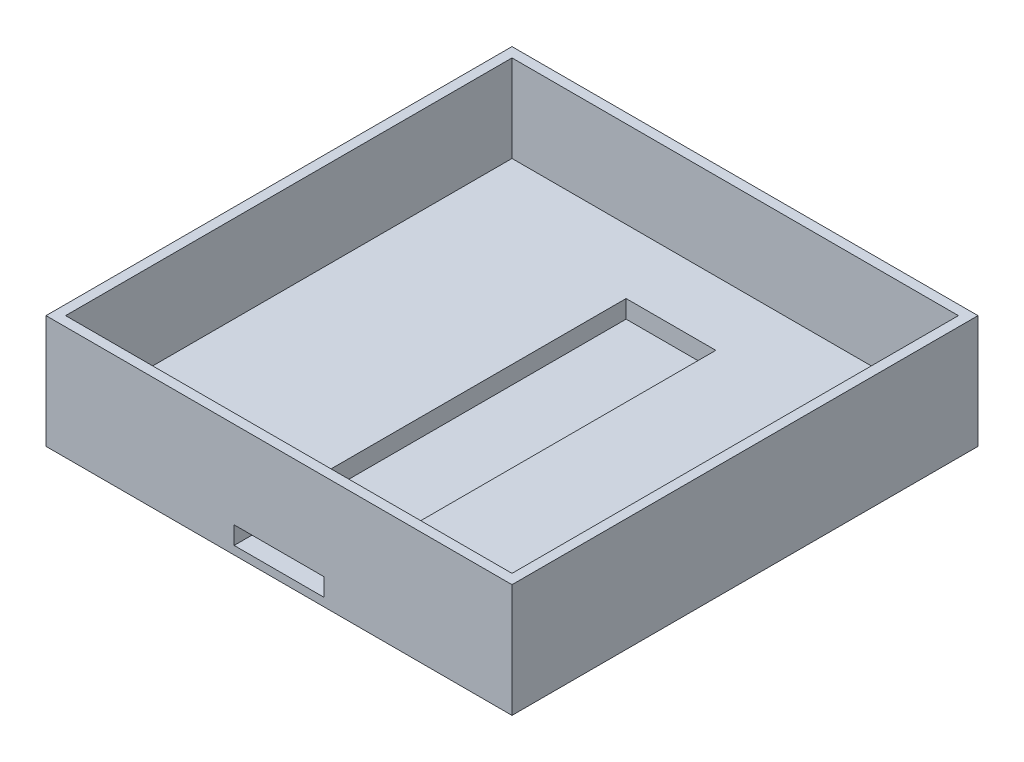
SolidWorks part; units mm, degrees
ref_plane "Front Plane" through (0, 0, 0) normal (0, 0, 1) x (1, 0, 0)
ref_plane "Top Plane" through (0, 0, 0) normal (0, 1, 0) x (1, 0, 0)
ref_plane "Right Plane" through (0, 0, 0) normal (1, 0, 0) x (0, 0, -1)
sketch "Sketch2" plane through (0, 0, 0) normal (0, 1, 0) x (1, 0, 0)
  line L1 (-53.5, -53.5) -> (53.5, -53.5)
  line L2 (-53.5, -53.5) -> (-53.5, 53.5)
  line L3 (-53.5, 53.5) -> (53.5, 53.5)
  line L4 (53.5, -53.5) -> (53.5, 53.5)
  line L5 (-53.5, -53.5) -> (53.5, 53.5) construction
  line L6 (-53.5, 53.5) -> (53.5, -53.5) construction
  point P0 (0, 0)
  dimension "D1" = 107
  dimension "D2" = 107
extrude "Boss-Extrude1" add sketch "Sketch2" along normal blind 8
sketch "Sketch4" plane through (0, 8, 0) normal (0, 1, 0) x (1, 0, 0)
  line L1 (-51, -51) -> (51, -51)
  line L2 (-51, -51) -> (-51, 51)
  line L3 (-51, 51) -> (51, 51)
  line L4 (51, -51) -> (51, 51)
  line L5 (-51, -51) -> (51, 51) construction
  line L6 (-51, 51) -> (51, -51) construction
  point P0 (0, 0)
  dimension "D1" = 102
  dimension "D2" = 102
sketch "Sketch14" plane through (0, 8, 0) normal (0, 1, 0) x (1, 0, 0)
  line L0 (-53.5, -53.5) -> (-53.5, 53.5) construction
  line L1 (-53.5, -53.5) -> (53.5, -53.5)
  line L2 (-53.5, -53.5) -> (-53.5, 53.5)
  line L3 (-53.5, 53.5) -> (53.5, 53.5)
  line L4 (53.5, -53.5) -> (53.5, 53.5)
  line L5 (-53.5, -53.5) -> (53.5, 53.5) construction
  line L6 (-53.5, 53.5) -> (53.5, -53.5) construction
  line L7 (-53.5, 53.5) -> (53.5, 53.5) construction
  point P0 (0, 0)
extrude "Boss-Extrude2" add sketch "Sketch14" along normal blind 18
sketch "Sketch15" plane through (0, 26, 0) normal (0, 1, 0) x (1, 0, 0)
  line L1 (-51.25, 51.25) -> (51.25, 51.25)
  line L2 (-51.25, 51.25) -> (-51.25, -51.25)
  line L3 (-51.25, -51.25) -> (51.25, -51.25)
  line L4 (51.25, 51.25) -> (51.25, -51.25)
  line L5 (-51.25, 51.25) -> (51.25, -51.25) construction
  line L6 (-51.25, -51.25) -> (51.25, 51.25) construction
  point P0 (0, 0)
  dimension "D1" = 102.5
extrude "Cut-Extrude4" cut sketch "Sketch15" against normal blind 20
sketch "Sketch12" plane through (0, 6, 0) normal (0, 1, 0) x (1, 0, 0)
  line L0 (-10.3, -53.5) -> (10.3, -53.5)
  line L1 (-10.3, -53.5) -> (-10.3, 36.5001)
  line L2 (10.3, -53.5) -> (10.3, 36.5001)
  line L3 (-10.3, 36.5001) -> (10.3, 36.5001)
  line L5 (0, 36.5001) -> (0, 0) construction
  line L6 (-53.5, -53.5) -> (53.5, -53.5) construction
  point P10 (0, 27.8489)
  dimension "D1" = 20.6
  dimension "D2" = 90.0001
extrude "Cut-Extrude3" cut sketch "Sketch12" against normal blind 4.1
